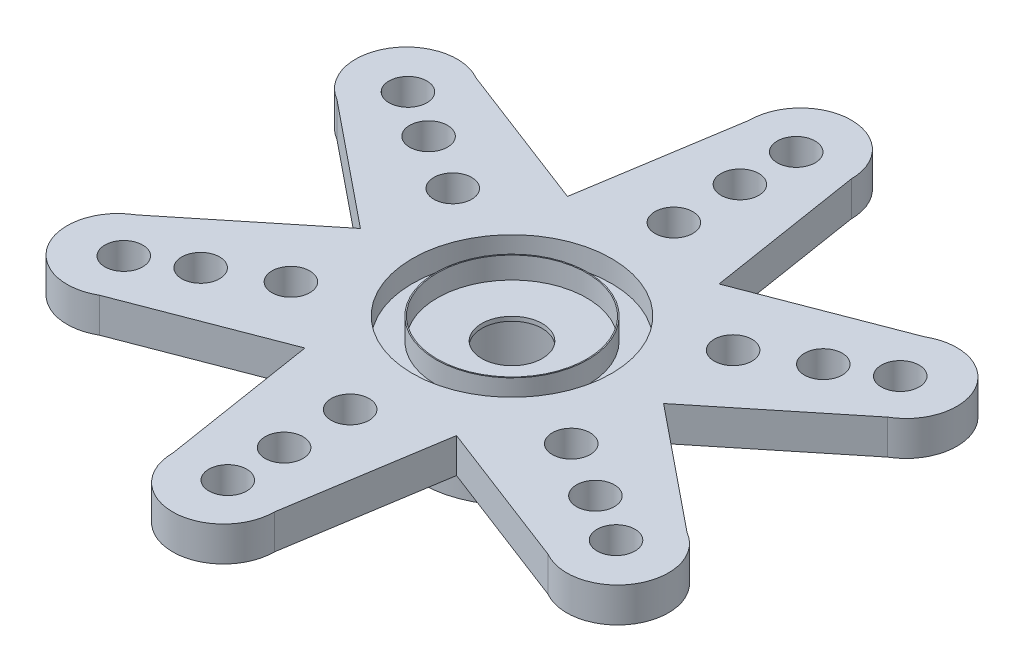
SolidWorks part; units mm, degrees
material "Caucho natural"
ref_plane "Alzado" through (0, 0, 0) normal (0, 0, 1) x (1, 0, 0)
ref_plane "Planta" through (0, 0, 0) normal (0, 1, 0) x (1, 0, 0)
ref_plane "Vista lateral" through (0, 0, 0) normal (1, 0, 0) x (0, 0, -1)
sketch "Croquis1" plane through (0, 0, 0) normal (0, 1, 0) x (1, 0, 0)
  line L0 (-2.35, 13.3217) -> (2.35, 13.3217)
  line L1 (-2.35, 13.3217) -> (-3.5, 6.0622)
  line L2 (2.35, 13.3217) -> (3.5, 6.0622)
  line L3 (-3.5, 6.0622) -> (3.5, 6.0622)
  line L4 (3.5, 6.0622) -> (7, 0)
  line L5 (12.7119, 4.6257) -> (7, 0)
  line L6 (10.3619, 8.696) -> (12.7119, 4.6257)
  line L7 (10.3619, 8.696) -> (3.5, 6.0622)
  line L8 (7, 0) -> (3.5, -6.0622)
  line L9 (10.3619, -8.696) -> (3.5, -6.0622)
  line L10 (12.7119, -4.6257) -> (10.3619, -8.696)
  line L11 (12.7119, -4.6257) -> (7, 0)
  line L12 (3.5, -6.0622) -> (-3.5, -6.0622)
  line L13 (-2.35, -13.3217) -> (-3.5, -6.0622)
  line L14 (2.35, -13.3217) -> (-2.35, -13.3217)
  line L15 (2.35, -13.3217) -> (3.5, -6.0622)
  line L16 (-3.5, -6.0622) -> (-7, 0)
  line L17 (-12.7119, -4.6257) -> (-7, 0)
  line L18 (-10.3619, -8.696) -> (-12.7119, -4.6257)
  line L19 (-10.3619, -8.696) -> (-3.5, -6.0622)
  line L20 (-7, 0) -> (-3.5, 6.0622)
  line L21 (-10.3619, 8.696) -> (-3.5, 6.0622)
  line L22 (-12.7119, 4.6257) -> (-10.3619, 8.696)
  line L23 (-12.7119, 4.6257) -> (-7, 0)
  circle A1 centre (0, 0) radius 7
  circle A3 centre (0, 13.3217) radius 2.35
  circle A4 centre (11.5369, 6.6608) radius 2.35
  circle A5 centre (11.5369, -6.6608) radius 2.35
  circle A6 centre (0, -13.3217) radius 2.35
  circle A7 centre (-11.5369, -6.6608) radius 2.35
  circle A8 centre (-11.5369, 6.6608) radius 2.35
  dimension "D3" = 10.3619
  dimension "D4" = 11.5369
  dimension "D1" = 4.7
  dimension "D2" = 14
extrude "Saliente-Extruir1" add sketch "Croquis1" along normal blind 1.6
sketch "Croquis3" plane through (0, 0, 0) normal (0, -1, 0) x (1, 0, 0)
  circle A0 centre (0, 0) radius 4.2
  dimension "D1" = 8.4
extrude "Saliente-Extruir2" add sketch "Croquis3" along normal blind 3
sketch "Croquis4" plane through (0, 1.6, 0) normal (0, 1, 0) x (1, 0, 0)
  circle A0 centre (0, 0) radius 4.6
  dimension "D1" = 9.2
extrude "Cortar-Extruir1" cut sketch "Croquis4" against normal blind 1
sketch "Croquis5" plane through (0, 0.6, 0) normal (0, 1, 0) x (1, 0, 0)
  circle A0 centre (0, 0) radius 3.5
  circle A1 centre (0, 0) radius 3.45
  dimension "D1" = 0.05
  dimension "D2" = 7
extrude "Saliente-Extruir3" add sketch "Croquis5" along normal blind 1
sketch "Croquis6" plane through (0, 1.6, 0) normal (0, 1, 0) x (1, 0, 0)
  line L0 (13.5721, 7.8358) -> (0, 0) construction
  circle A0 centre (0, 0) radius 7.475 construction
  circle A1 centre (0, 0) radius 10.525 construction
  circle A2 centre (0, 0) radius 13.125 construction
  circle A3 centre (11.3666, 6.5625) radius 0.875
  arc A5 (12.7119, 4.6257) -> (10.3619, 8.696) centre (11.5369, 6.6608) ccw construction
  circle A6 centre (9.1149, 5.2625) radius 0.875
  circle A7 centre (6.4735, 3.7375) radius 0.875
  circle A8 centre (11.3666, -6.5625) radius 0.875
  circle A9 centre (9.1149, -5.2625) radius 0.875
  circle A10 centre (6.4735, -3.7375) radius 0.875
  circle A11 centre (0, -13.125) radius 0.875
  circle A12 centre (0, -10.525) radius 0.875
  circle A13 centre (0, -7.475) radius 0.875
  circle A14 centre (-11.3666, -6.5625) radius 0.875
  circle A15 centre (-9.1149, -5.2625) radius 0.875
  circle A16 centre (-6.4735, -3.7375) radius 0.875
  circle A17 centre (-11.3666, 6.5625) radius 0.875
  circle A18 centre (-9.1149, 5.2625) radius 0.875
  circle A19 centre (-6.4735, 3.7375) radius 0.875
  circle A20 centre (0, 13.125) radius 0.875
  circle A21 centre (0, 10.525) radius 0.875
  circle A22 centre (0, 7.475) radius 0.875
  dimension "D1" = 26.25
  dimension "D2" = 2.6
  dimension "D3" = 5.65
  dimension "D4" = 1.75
  dimension "D5" = 1.75
  dimension "D6" = 1.75
  dimension "D7" = 6
extrude "Cortar-Extruir2" cut sketch "Croquis6" against normal through all
sketch "Croquis7" plane through (0, 0.6, 0) normal (0, 1, 0) x (1, 0, 0)
  circle A0 centre (0, 0) radius 1.4
  dimension "D1" = 2.8
extrude "Cortar-Extruir3" cut sketch "Croquis7" against normal through all
sketch "Croquis8" plane through (0, -3, 0) normal (0, -1, 0) x (1, 0, 0)
  circle A0 centre (0, 0) radius 2.65
  circle A1 centre (0, 0) radius 4.2 construction
  dimension "D1" = 1.55
extrude "Cortar-Extruir4" cut sketch "Croquis8" against normal blind 3.4
